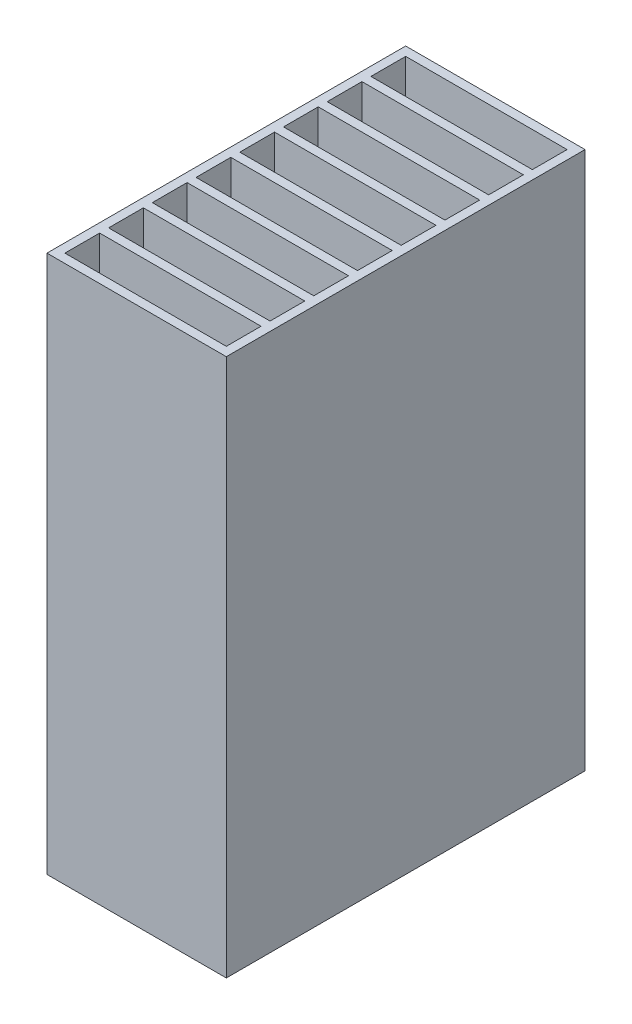
SolidWorks part; units mm, degrees
ref_plane "Plan de face" through (0, 0, 0) normal (1, 0, 0) x (0, 1, 0)
ref_plane "Plan de dessus" through (0, 0, 0) normal (0, 0, 1) x (0, 1, 0)
ref_plane "Plan de droite" through (0, 0, 0) normal (0, 1, 0) x (-1, 0, 0)
sketch "Esquisse1" plane through (0, 0, 0) normal (1, 0, 0) x (0, 1, 0)
  line L1 (30, -20) -> (-30, -20)
  line L2 (30, -20) -> (30, 20)
  line L3 (30, 20) -> (-30, 20)
  line L4 (-30, -20) -> (-30, 20)
  line L5 (30, -20) -> (-30, 20) construction
  line L6 (30, 20) -> (-30, -20) construction
  point P0 (0, 0)
  dimension "D1" = 40
  dimension "D2" = 60
extrude "Boss.-Extru.1" add sketch "Esquisse1" along normal blind 20
sketch "Esquisse2" plane through (0, -30, 0) normal (0, -1, 0) x (1, 0, 0)
  line L11 (19, 19) -> (1, 19)
  line L20 (19, 19) -> (19, 15.125)
  line L21 (19, 15.125) -> (1, 15.125)
  line L30 (1, 19) -> (1, 15.125)
  line L40 (20, 20) -> (0, 20) construction
  line L50 (19, 14.125) -> (1, 14.125)
  line L51 (19, 14.125) -> (19, 10.25)
  line L52 (19, 10.25) -> (1, 10.25)
  line L53 (1, 14.125) -> (1, 10.25)
  line L54 (19, 9.25) -> (1, 9.25)
  line L55 (19, 9.25) -> (19, 5.375)
  line L56 (19, 5.375) -> (1, 5.375)
  line L57 (1, 9.25) -> (1, 5.375)
  line L58 (19, 4.375) -> (1, 4.375)
  line L59 (19, 4.375) -> (19, 0.5)
  line L60 (19, 0.5) -> (1, 0.5)
  line L61 (1, 4.375) -> (1, 0.5)
  line L66 (19, -0.5) -> (1, -0.5)
  line L67 (19, -0.5) -> (19, -4.375)
  line L68 (19, -4.375) -> (1, -4.375)
  line L69 (1, -0.5) -> (1, -4.375)
  line L70 (19, -5.375) -> (1, -5.375)
  line L71 (19, -5.375) -> (19, -9.25)
  line L72 (19, -9.25) -> (1, -9.25)
  line L73 (1, -5.375) -> (1, -9.25)
  line L74 (19, -10.25) -> (1, -10.25)
  line L75 (19, -10.25) -> (19, -14.125)
  line L76 (19, -14.125) -> (1, -14.125)
  line L77 (1, -10.25) -> (1, -14.125)
  line L78 (19, -15.125) -> (1, -15.125)
  line L79 (19, -15.125) -> (19, -19)
  line L80 (19, -19) -> (1, -19)
  line L81 (1, -15.125) -> (1, -19)
  line L82 (0, 20) -> (0, -20) construction
  line L84 (20, 20) -> (20, -20) construction
  dimension "D1" = 1
  dimension "D2" = 3.875
  dimension "D3" = 1
  dimension "D4" = 3.875
  dimension "D5" = 1
  dimension "D6" = 3.875
  dimension "D7" = 1
  dimension "D8" = 3.875
  dimension "D9" = 1
  dimension "D10" = 3.875
  dimension "D11" = 1
  dimension "D12" = 1
  dimension "D13" = 3.875
  dimension "D14" = 3.875
  dimension "D15" = 1
  dimension "D16" = 3.875
  dimension "D17" = 1
  dimension "D18" = 1
extrude "Enlèv. mat.-Extru.1" cut sketch "Esquisse2" against normal through all
